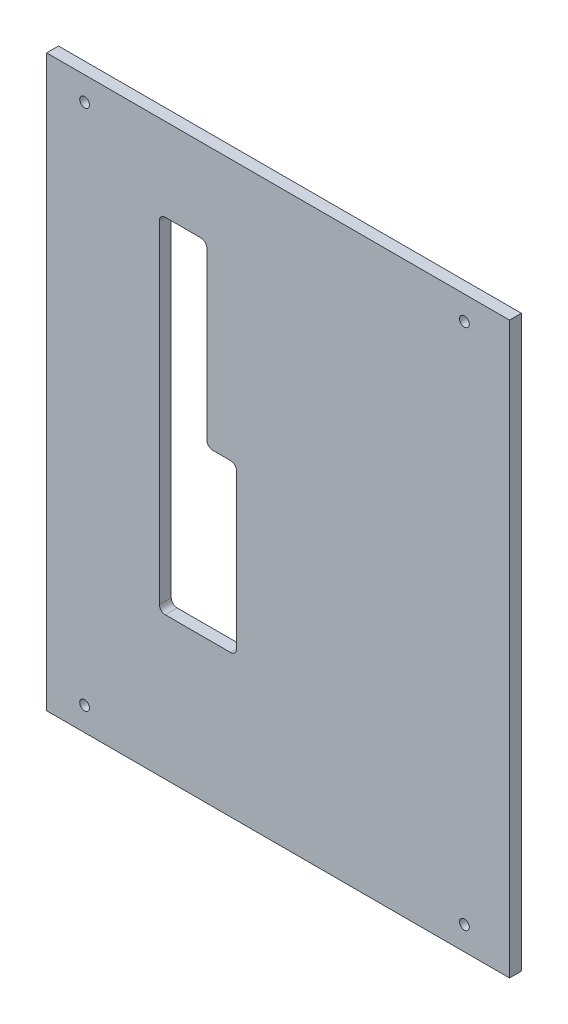
SolidWorks part; units mm, degrees
ref_plane "Plan de face" through (0, 0, 0) normal (0, 0, 1) x (1, 0, 0)
ref_plane "Plan de dessus" through (0, 0, 0) normal (0, 1, 0) x (1, 0, 0)
ref_plane "Plan de droite" through (0, 0, 0) normal (1, 0, 0) x (0, 0, -1)
sketch "Esquisse1" plane through (0, 0, 0) normal (0, 0, 1) x (1, 0, 0)
  line L0 (0, 138.1871) -> (0, -161.4958) construction
  line L6 (-52.5, 85) -> (-52.5, 10)
  line L12 (75, -120) -> (-120, -120)
  line L13 (-211.9518, 0) -> (287.0439, 0) construction
  line L18 (80, 178.5365) -> (80, -130.49) construction
  line L19 (-80, 178.5365) -> (-80, -130.49) construction
  line L20 (75, -120) -> (75, 120)
  line L21 (75, 120) -> (-120, 120)
  line L22 (-120, -120) -> (-120, 120)
  line L23 (75, -120) -> (-120, 120) construction
  line L24 (75, 120) -> (-120, -120) construction
  line L25 (75, -120) -> (-120, -120) construction
  line L26 (75, -120) -> (75, 120) construction
  line L27 (75, 120) -> (-120, 120) construction
  line L28 (-120, -120) -> (-120, 120) construction
  line L29 (75, -120) -> (-120, 120) construction
  line L30 (75, 120) -> (-120, -120) construction
  line L31 (-40, -60) -> (-72.5, -60)
  line L32 (-40, -60) -> (-40, 85)
  line L33 (-40, 85) -> (-72.5, 85)
  line L34 (-72.5, -60) -> (-72.5, 85)
  line L35 (-40, -60) -> (-72.5, 85) construction
  line L36 (-40, 85) -> (-72.5, -60) construction
  line L37 (-52.5, 10) -> (-40, 10)
  circle A0 centre (-104, 110) radius 2.05
  circle A1 centre (56, 110) radius 2.05
  circle A2 centre (56, -110) radius 2.05
  circle A3 centre (-104, -110) radius 2.05
  point P0 (0, 0)
  point P1 (-22.5, 0)
  point P5 (0, 0)
  point P9 (-22.5, 0)
  point P30 (-56.25, 12.5)
  dimension "D2" = 4.1
  dimension "D1" = 195
  dimension "D3" = 24
  dimension "D4" = 24
  dimension "D5" = 240
  dimension "D6" = 5
  dimension "D7" = 10
  dimension "D8" = 240
  dimension "D9" = 160
  dimension "D10" = 195
  dimension "D11" = 47.5
  dimension "D12" = 60
  dimension "D13" = 145
  dimension "D14" = 32.5
  dimension "D15" = 12.5
  dimension "D16" = 75
extrude "Boss.-Extru.1" add sketch "Esquisse1" along normal blind 5 contours L22 L12 L20 L21 A2 A1 A0 L31 L34 L33 L32 A3 | L6 L37 L32 L33
fillet "Congé1" radius 2.5 6 edges at (-72.5, -60, 2.5) (-40, -60, 2.5) (-52.5, 85, 2.5) (-72.5, 85, 2.5) (-40, 10, 2.5) (-52.5, 10, 2.5)
